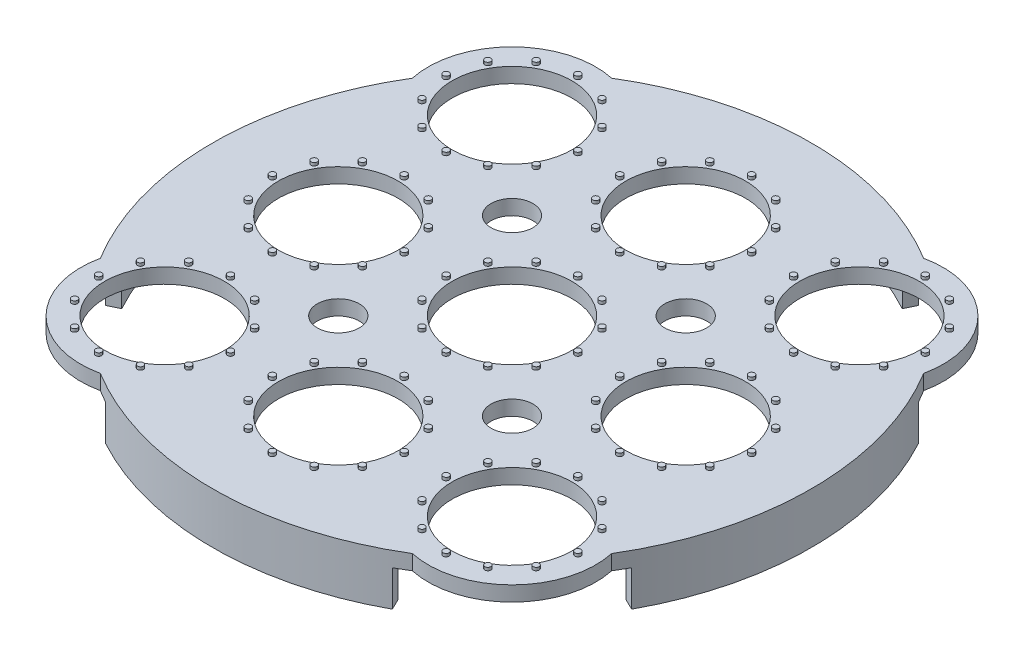
SolidWorks part; units mm, degrees
ref_plane "Front Plane" through (0, 0, 0) normal (0, 0, 1) x (1, 0, 0)
ref_plane "Top Plane" through (0, 0, 0) normal (0, 1, 0) x (1, 0, 0)
ref_plane "Right Plane" through (0, 0, 0) normal (1, 0, 0) x (0, 0, -1)
sketch "Sketch1" plane through (0, 0, 0) normal (0, 1, 0) x (1, 0, 0)
  arc A0 (26.0405, 42.6836) -> (-26.0405, 42.6836) centre (0, 0) ccw
  circle A1 centre (0, 0) radius 14 construction
  circle A2 centre (29, 0) radius 14 construction
  circle A3 centre (-29, 0) radius 14 construction
  arc A4 (26.0405, -42.6836) -> (42.6836, -26.0405) centre (29, -29) ccw
  circle A5 centre (0, -29) radius 14 construction
  arc A6 (-42.6836, -26.0405) -> (-26.0405, -42.6836) centre (-29, -29) ccw
  arc A7 (42.6836, 26.0405) -> (26.0405, 42.6836) centre (29, 29) ccw
  circle A8 centre (0, 29) radius 14 construction
  arc A9 (-26.0405, 42.6836) -> (-42.6836, 26.0405) centre (-29, 29) ccw
  arc A10 (-42.6836, 26.0405) -> (-42.6836, -26.0405) centre (0, 0) ccw
  arc A11 (-26.0405, -42.6836) -> (26.0405, -42.6836) centre (0, 0) ccw
  arc A12 (42.6836, -26.0405) -> (42.6836, 26.0405) centre (0, 0) ccw
  dimension "D1" = 100
  dimension "D2" = 28
  dimension "D5" = 29
  dimension "D8" = 29
  dimension "D3" = 29
  dimension "D4" = 29
  dimension "D6" = 3
  dimension "D7" = 2
extrude "Boss-Extrude1" add sketch "Sketch1" along normal blind 2.5
sketch "Sketch2" plane through (0, 2.5, 0) normal (0, 1, 0) x (1, 0, 0)
  circle A1 centre (-29, -29) radius 10
  dimension "D1" = 29
  dimension "D3" = 20
  dimension "D2" = 29
extrude "Cut-Extrude1" cut sketch "Sketch2" against normal through all
pattern_linear "LPattern1" count 3 spacing 29 along (1, 0, 0) count 3 spacing 29 along (0, 0, -1) of "Cut-Extrude1"
sketch "Sketch4" plane through (0, 2.5, 0) normal (0, 1, 0) x (1, 0, 0)
  circle A1 centre (-29, -29) radius 10 construction
  circle A2 centre (-29, -29) radius 10 construction
  circle A3 centre (-29, -18) radius 0.5
  dimension "D1" = 1
  dimension "D2" = 11
extrude "Boss-Extrude2" add sketch "Sketch4" along normal blind 0.5 contours A3
pattern_circular "CirPattern1" count 12 over 360 about axis through (-29, 0, 29) along (0, 1, 0) of "Boss-Extrude2"
pattern_linear "LPattern2" count 3 spacing 29 along (0, 0, -1) count 3 spacing 29 along (1, 0, 0) of "Boss-Extrude2", "CirPattern1"
sketch "Sketch5" plane through (0, 2.5, 0) normal (0, 1, 0) x (1, 0, 0)
  circle A0 centre (14.5, -14.5) radius 3.5
  circle A1 centre (29, 0) radius 10 construction
  circle A2 centre (0, -29) radius 10 construction
  dimension "D1" = 14.5
  dimension "D3" = 7
  dimension "D2" = 14.5
extrude "Cut-Extrude2" cut sketch "Sketch5" against normal through all contours A0
mirror "Mirror1" about plane through (0, 0, 0) normal (1, 0, 0) of "Cut-Extrude2"
mirror "Mirror2" about plane through (0, 0, 0) normal (0, 0, 1) of "Mirror1", "Cut-Extrude2"
sketch "Sketch6" plane through (0, 0, 0) normal (0, -1, 0) x (-1, 0, 0)
  line L0 (-23.9246, -43.9046) -> (-23.0478, -42.107)
  line L1 (23.9246, -43.9046) -> (23.0478, -42.107)
  arc A1 (-26.0405, -42.6836) -> (26.0405, -42.6836) centre (0, 0) ccw construction
  arc A2 (-23.0478, -42.107) -> (23.0478, -42.107) centre (0, 0) ccw
  arc A3 (-23.9246, -43.9046) -> (23.9246, -43.9046) centre (0, 0) ccw
  point P3 (0, -50)
  point P10 (0, -48.0021)
  dimension "D2" = 52
  dimension "D1" = 2
extrude "Boss-Extrude3" add sketch "Sketch6" along normal blind 6
pattern_circular "CirPattern2" count 4 over 360 about axis through (0, 0, 0) along (0, 1, 0) of "Boss-Extrude3"
